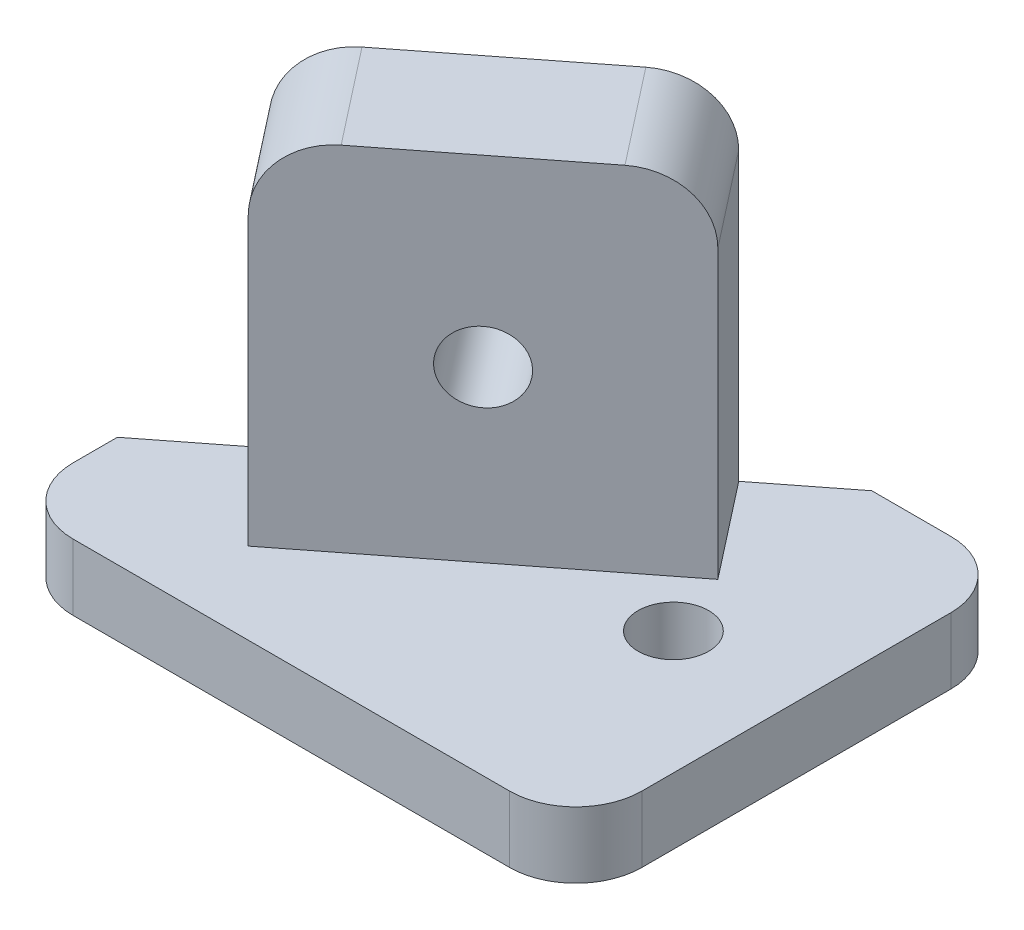
SolidWorks part; units mm, degrees
ref_plane "前视基准面" through (0, 0, 0) normal (0, 0, 1) x (1, 0, 0)
ref_plane "上视基准面" through (0, 0, 0) normal (0, 1, 0) x (1, 0, 0)
ref_plane "右视基准面" through (0, 0, 0) normal (1, 0, 0) x (0, 0, -1)
sketch "草图1" plane through (0, 0, 0) normal (0, 1, 0) x (1, 0, 0)
  line L0 (0, 5) -> (19.1991, 20)
  line L1 (0, 0) -> (25.7798, 0)
  line L2 (0, 0) -> (0, 5)
  line L3 (19.1991, 20) -> (25.7798, 20)
  line L4 (25.7798, 0) -> (25.7798, 20)
  line L5 (20, 10) -> (-49980, 10) construction
  circle A0 centre (20.2069, 10) radius 1.6
  point P12 (25.7798, 10)
  dimension "D5" = 3.2
  dimension "D2" = 20
  dimension "D3" = 38
  dimension "D4" = 5
extrude "凸台-拉伸1" add sketch "草图1" along normal blind 3
sketch "草图2" plane through (0, 3, 0) normal (0, 1, 0) x (1, 0, 0)
  line L0 (3.8618, 8.0172) -> (7.2399, 3.6935)
  line L1 (19.1991, 20) -> (0, 5) construction
  line L2 (7.2399, 3.6935) -> (19.1914, 13.031)
  line L3 (19.1914, 13.031) -> (15.8133, 17.3547)
  line L4 (15.8133, 17.3547) -> (3.8618, 8.0172)
  circle A0 centre (20.2069, 10) radius 3 construction
  dimension "D1" = 6
extrude "凸台-拉伸2" add sketch "草图2" along normal blind 16
sketch "草图4" plane through (-2.4257, 0, -3.1048) normal (-0.6157, 0, -0.788) x (-0.788, 0, 0.6157)
  line L0 (-23.1457, 3) -> (-7.979, 3) construction
  line L1 (-15.5624, 19) -> (-15.5624, 3) construction
  line L2 (-23.1457, 19) -> (-7.979, 19) construction
  line L3 (-23.1457, 11) -> (-7.979, 11) construction
  line L4 (-23.1457, 19) -> (-23.1457, 3) construction
  line L5 (-7.979, 19) -> (-7.979, 3) construction
  circle A0 centre (-15.5624, 10.6819) radius 1.6
  dimension "D1" = 3.2
extrude "切除-拉伸2" cut sketch "草图4" against normal through all
fillet "圆角1" radius 3 5 edges at (5.5509, 19, -5.8553) (17.5024, 19, -15.1929) (25.7798, 1.5, -20) (0, 1.5, 0) (25.7798, 1.5, 0)
